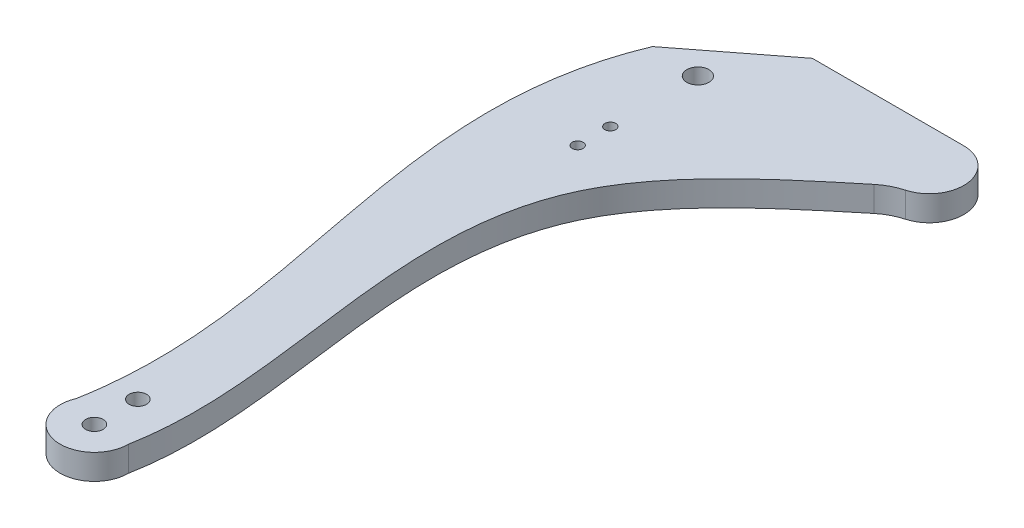
SolidWorks part; units mm, degrees
ref_plane "Front Plane" through (0, 0, 0) normal (0, 0, 1) x (1, 0, 0)
ref_plane "Top Plane" through (0, 0, 0) normal (0, 1, 0) x (1, 0, 0)
ref_plane "Right Plane" through (0, 0, 0) normal (1, 0, 0) x (0, 0, -1)
sketch "Sketch1" plane through (0, 0, 0) normal (0, 1, 0) x (1, 0, 0)
  line L0 (-16.1449, 8.454) -> (10.8777, 8.454)
  line L1 (-16.1449, 8.454) -> (-32.2175, -3.9875)
  line L2 (-23.6206, -4.479) -> (-23.6206, -112.139) construction
  circle A0 centre (-23.6206, -4.479) radius 1.975
  arc A1 (12.5128, -3.6032) -> (10.8777, 8.454) centre (10.8777, 2.3145) ccw
  circle A2 centre (-23.6206, -112.139) radius 1.555
  circle A3 centre (-23.6206, -104.379) radius 1.555
  arc A4 (-29.2395, -109.7574) -> (-17.5177, -112.139) centre (-23.6206, -112.139) ccw
  arc A5 (12.5128, -3.6032) -> (8.8241, -5.5185) centre (15.1759, -13.2421) ccw
  circle A6 centre (-23.6206, -25.919) radius 0.97
  circle A7 centre (-23.6206, -20.099) radius 0.97
  spline S0 degree 3 poles (-32.2175, -3.9875) (-42.2065, -27.8278) (-29.5614, -63.9823) (-27.3902, -99.665) (-29.2395, -109.7574) knots 0 0 0 0 0.696305 0.977824 0.977824 0.977824 0.977824
  spline S1 degree 3 poles (8.8241, -5.5185) (4.9325, -8.7188) (-4.696, -16.5859) (-31.4891, -46.9438) (-12.8947, -87.3265) (-17.5177, -112.139) knots 0.023478 0.023478 0.023478 0.023478 0.154944 0.330833 1 1 1 1
  dimension "D1" = 10
  dimension "D4" = 3.11
  dimension "D5" = 3.11
  dimension "D7" = 1.94
  dimension "D9" = 1.94
  dimension "D2" = 107.66
  dimension "D3" = 99.9
  dimension "D6" = 21.44
  dimension "D8" = 5.82
extrude "Boss-Extrude1" add sketch "Sketch1" along normal blind 4.5
